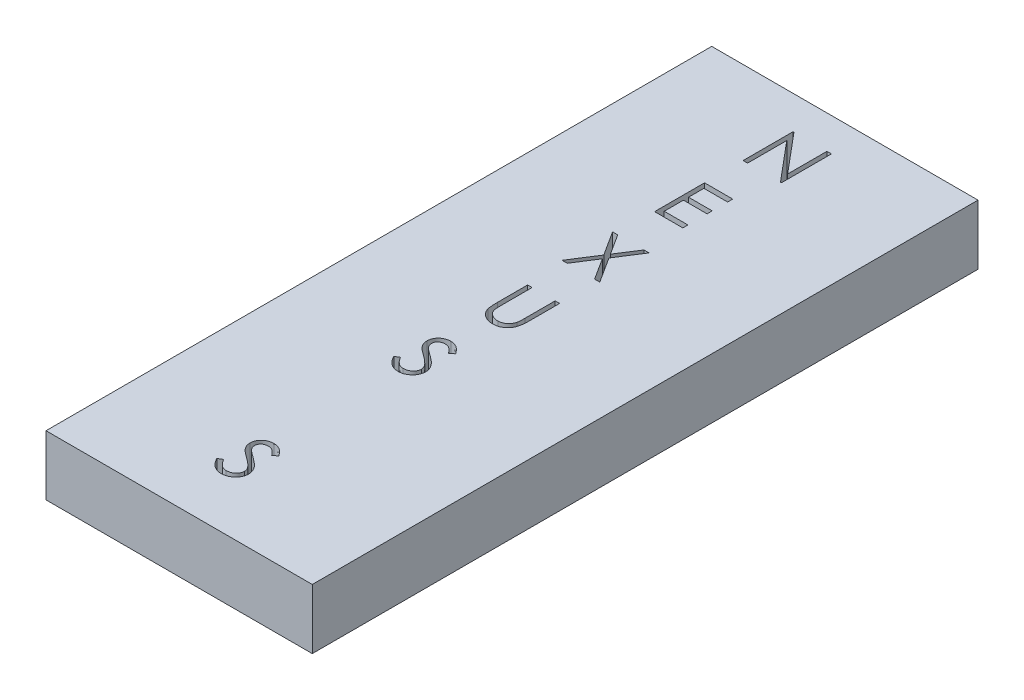
SolidWorks part; units mm, degrees
ref_plane "Front Plane" through (0, 0, 0) normal (0, 0, 1) x (1, 0, 0)
ref_plane "Top Plane" through (0, 0, 0) normal (0, 1, 0) x (1, 0, 0)
ref_plane "Right Plane" through (0, 0, 0) normal (1, 0, 0) x (0, 0, -1)
sketch "Sketch1" plane through (0, 0, 0) normal (0, 1, 0) x (1, 0, 0)
  line L1 (0, 0) -> (50.8, 0)
  line L2 (0, 0) -> (0, 127)
  line L3 (0, 127) -> (50.8, 127)
  line L4 (50.8, 0) -> (50.8, 127)
  dimension "D1" = 50.8
  dimension "D2" = 127
extrude "Boss-Extrude1" add sketch "Sketch1" along normal blind 11.43
sketch "Sketch2" plane through (0, 11.43, 0) normal (0, 1, 0) x (1, 0, 0)
  line L2 (50.8, 127) -> (0, 127) construction
  line L4 (0, 127) -> (0, 0) construction
  text T0 "N\r\nE\r\nX\r\nU\r\nS\r\n\r\nS" font "Century Gothic" height in points 36
  dimension "D1" = 15.875
  dimension "D2" = 20.6375
extrude "Cut-Extrude1" cut sketch "Sketch2" against normal through all
